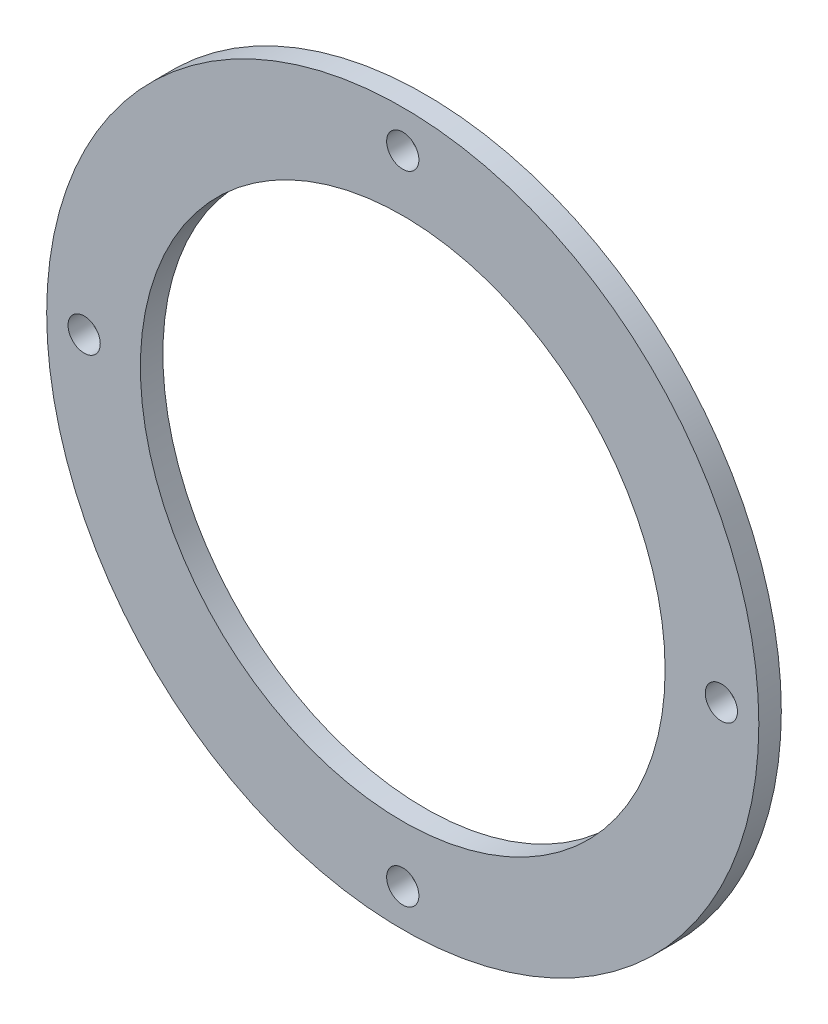
SolidWorks part; units mm, degrees
ref_plane "前视基准面" through (0, 0, 0) normal (0, 0, 1) x (1, 0, 0)
ref_plane "上视基准面" through (0, 0, 0) normal (0, 1, 0) x (1, 0, 0)
ref_plane "右视基准面" through (0, 0, 0) normal (1, 0, 0) x (0, 0, -1)
other "Configuration Table"
sketch "草图1" plane through (0, 0, 0) normal (0, 0, 1) x (1, 0, 0)
  circle A0 centre (0, 0) radius 47.5
  circle A1 centre (0, 0) radius 35
  dimension "D1" = 95
  dimension "D2" = 70
extrude "凸台-拉伸1" add sketch "草图1" along normal blind 3
sketch "草图2" plane through (0, 0, 3) normal (0, 0, 1) x (1, 0, 0)
  circle A0 centre (42.5, 0) radius 2.15
  circle A1 centre (0, 0) radius 47.5 construction
  circle A2 centre (0, -42.5) radius 2.15
  circle A3 centre (-42.5, 0) radius 2.15
  circle A4 centre (0, 42.5) radius 2.15
  point P3 (47.5, 0)
  point P14 (0, 0)
  dimension "D1" = 4.3
  dimension "D2" = 5
  dimension "D3" = 4
extrude "切除-拉伸1" cut sketch "草图2" against normal up to next
